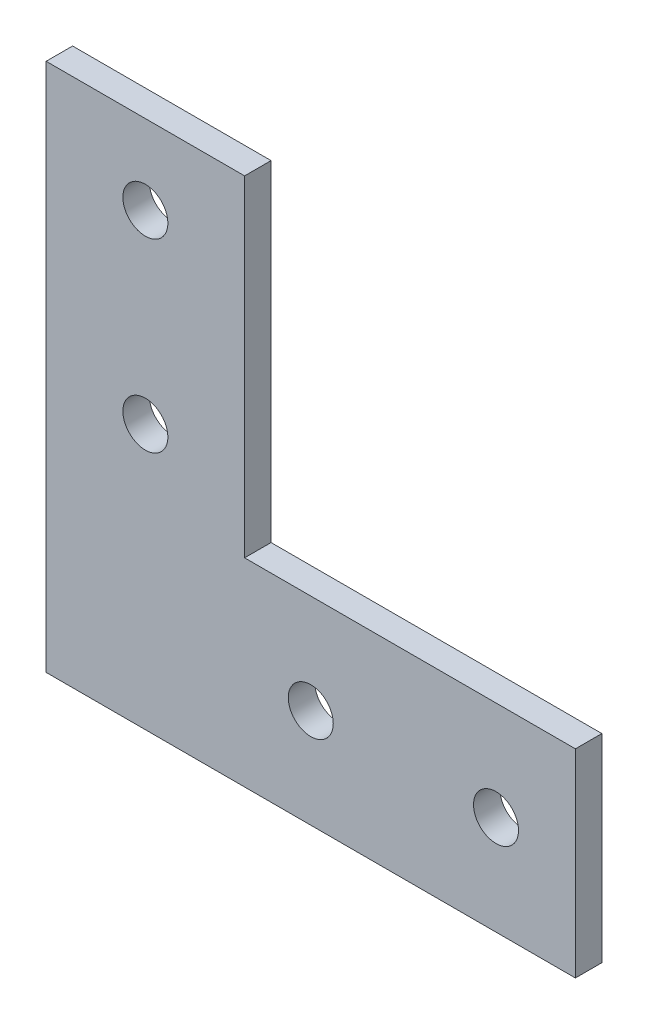
SolidWorks part; units mm, degrees
ref_plane "前视基准面" through (0, 0, 0) normal (0, 0, 1) x (1, 0, 0)
ref_plane "上视基准面" through (0, 0, 0) normal (0, 1, 0) x (1, 0, 0)
ref_plane "右视基准面" through (0, 0, 0) normal (1, 0, 0) x (0, 0, -1)
other "Configuration Table"
sketch "草图1" plane through (0, 0, 0) normal (0, 0, 1) x (1, 0, 0)
  line L0 (0, 0) -> (40, 0)
  line L1 (40, 0) -> (40, 15)
  line L2 (40, 15) -> (15, 15)
  line L3 (15, 15) -> (15, 40)
  line L4 (15, 40) -> (0, 40)
  line L5 (0, 40) -> (0, 0)
  line L6 (20, 7.5) -> (-18.837, 7.5) construction
  line L7 (0, 0) -> (15, 15) construction
  circle A0 centre (20, 7.5) radius 1.7
  circle A1 centre (34, 7.5) radius 1.7
  circle A2 centre (7.5, 34) radius 1.7
  circle A3 centre (7.5, 20) radius 1.7
  dimension "D5" = 3.4
  dimension "D1" = 15
  dimension "D2" = 15
  dimension "D3" = 40
  dimension "D4" = 40
  dimension "D6" = 5
  dimension "D7" = 6
extrude "凸台-拉伸1" add sketch "草图1" along normal blind 2
